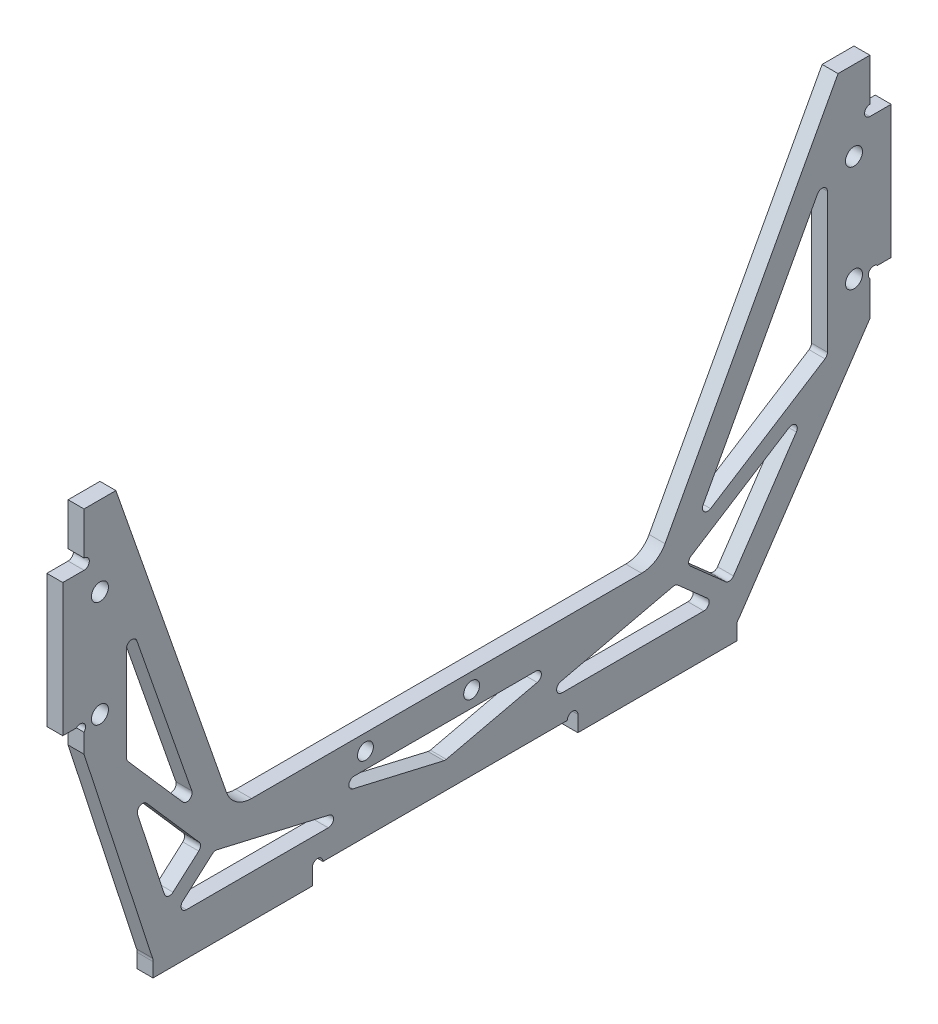
SolidWorks part; units mm, degrees
material "玻纤"
ref_plane "前视基准面" through (0, 0, 0) normal (0, 0, 1) x (1, 0, 0)
ref_plane "上视基准面" through (0, 0, 0) normal (0, 1, 0) x (1, 0, 0)
ref_plane "右视基准面" through (0, 0, 0) normal (1, 0, 0) x (0, 0, -1)
sketch "草图1" plane through (0, 0, 0) normal (1, 0, 0) x (0, 0, -1)
  line L0 (-74, -23) -> (74, -23)
  line L1 (-74, -40) -> (74, -40)
  line L2 (-74, -40) -> (-74, 40)
  line L3 (-74, 40) -> (74, 40)
  line L4 (74, -40) -> (74, 40)
  line L5 (-74, -40) -> (74, 40) construction
  line L6 (-74, 40) -> (74, -40) construction
  line L7 (-68, 40) -> (-46, -23)
  line L8 (34, -23) -> (68, 40)
  line L9 (-61, -40) -> (-74, -20.7267)
  line L10 (-61, -40) -> (-31, -40)
  line L11 (-61, -40) -> (-61, -43)
  line L12 (-61, -43) -> (-31, -43)
  line L13 (-31, -40) -> (-31, -43)
  line L14 (19, -40) -> (49, -40)
  line L15 (19, -40) -> (19, -43)
  line L16 (19, -43) -> (49, -43)
  line L17 (49, -40) -> (49, -43)
  line L18 (49, -40) -> (74, -2.936)
  point P0 (0, 0)
  dimension "D1" = 148
  dimension "D2" = 80
  dimension "D3" = 6
  dimension "D4" = 28
  dimension "D5" = 17
  dimension "D6" = 40
  dimension "D7" = 6
  dimension "D8" = 30
  dimension "D9" = 13
  dimension "D10" = 25
  dimension "D11" = 30
  dimension "D12" = 3
  dimension "D13" = 3
  dimension "D14" = 56
  dimension "D15" = 56
extrude "凸台-拉伸1" add sketch "草图1" along normal blind 3 contours L1 L4 L0 L2 | L7 L3 L2 L0 | L8 L0 L4 L3 | L13 L1 L11 L12 | L17 L1 L15 L16
sketch "草图2" plane through (3, 0, 0) normal (1, 0, 0) x (0, 0, -1)
  line L0 (-74, -20.7267) -> (-74, 40) construction
  line L1 (-74, 30) -> (-78, 30)
  line L2 (-74, 30) -> (-74, 5)
  line L3 (-74, 5) -> (-78, 5)
  line L4 (-78, 30) -> (-78, 5)
  line L5 (-31, -40) -> (19, -40) construction
  line L6 (74, -2.936) -> (74, 40) construction
  line L12 (74, 30) -> (78, 30)
  line L13 (74, 30) -> (74, 5)
  line L14 (74, 5) -> (78, 5)
  line L15 (78, 30) -> (78, 5)
  dimension "D1" = 4
  dimension "D2" = 25
  dimension "D3" = 45
  dimension "D4" = 4
extrude "凸台-拉伸2" add sketch "草图2" against normal blind 3
sketch "草图6" plane through (0, 0, 0) normal (-1, 0, 0) x (0, 0, 1)
  line L0 (-71, 40) -> (-71, 0) construction
  line L1 (-74, 40) -> (-68, 40) construction
  line L2 (-74, 40) -> (-74, 0) construction
  line L3 (-74, 0) -> (-68, 0) construction
  line L4 (-68, 40) -> (-68, 0) construction
  line L5 (0, 0) -> (0, -23) construction
  line L7 (46, -23) -> (-34, -23) construction
  line L8 (68, 40) -> (68, 0) construction
  line L9 (74, 0) -> (68, 0) construction
  line L10 (74, 40) -> (74, 0) construction
  line L11 (74, 40) -> (68, 40) construction
  line L12 (71, 40) -> (71, 0) construction
  circle A0 centre (-71, 25) radius 1.6
  circle A1 centre (-71, 5) radius 1.6
  circle A4 centre (71, 5) radius 1.6
  circle A5 centre (71, 25) radius 1.6
  dimension "D3" = 15
  dimension "D4" = 20
  dimension "D5" = 3.2
  dimension "D1" = 6
  dimension "D2" = 40
extrude "切除-拉伸4" cut sketch "草图6" against normal blind 4 contours A1 | A5 | A4 | A0
sketch "草图7" plane through (3, 0, 0) normal (1, 0, 0) x (0, 0, -1)
  line L0 (-66, 13.2098) -> (-66, -4.6242)
  line L3 (-53.6947, -16.1312) -> (-64.0559, 13.5395)
  line L5 (-68, 40) -> (-46, -23) construction
  line L6 (-78, 30) -> (-78, 5) construction
  line L7 (-65.7524, -5.2828) -> (-55.3913, -17.1195)
  line L9 (66, -4.4499) -> (66, 21.8078)
  line L18 (64.12, 22.2827) -> (42.5796, -17.6303)
  line L19 (34, -23) -> (68, 40) construction
  line L20 (78, 30) -> (78, 5) construction
  line L22 (-74, 0) -> (-61, -40)
  line L23 (-74, -20.7267) -> (-74, 5) construction
  line L24 (-61, -40) -> (-74, -20.7267)
  line L25 (-74, -20.7267) -> (-74, 0)
  line L26 (43.995, -18.9498) -> (65.5354, -5.2945)
  line L27 (-46, -23) -> (34, -23) construction
  line L28 (-62.2134, -13.8807) -> (-52.3073, -25.1974)
  line L29 (-52.3976, -26.6054) -> (-57.2363, -30.8807)
  line L30 (-58.8494, -30.4404) -> (-63.9168, -14.8484)
  line L31 (-55.3877, -33.2506) -> (-49.8314, -28.3412)
  line L32 (-48.9432, -28.1165) -> (-27.7828, -33.0259)
  line L33 (-28.0088, -35) -> (-54.7255, -35)
  line L34 (-23.1262, -29) -> (11.1262, -29)
  line L35 (11.3522, -30.9741) -> (-5.774, -34.9476)
  line L36 (-6.226, -34.9476) -> (-23.3522, -30.9741)
  line L37 (15.7828, -33.0259) -> (36.9432, -28.1165)
  line L38 (37.8314, -28.3412) -> (43.3877, -33.2506)
  line L39 (42.7255, -35) -> (16.0088, -35)
  line L40 (40.3205, -24.8313) -> (58.7839, -13.1266)
  line L41 (60.1484, -14.5304) -> (48.3069, -32.0861)
  line L42 (46.8157, -32.2763) -> (40.1938, -26.4253)
  line L43 (49, -40) -> (74, -2.936) construction
  line L44 (-6, -35) -> (-6, -40) construction
  line L45 (-31, -40) -> (19, -40) construction
  arc A0 (66, 21.8078) -> (64.12, 22.2827) centre (65, 21.8078) ccw
  arc A7 (-66, 13.2098) -> (-64.0559, 13.5395) centre (-65, 13.2098) cw
  circle A8 centre (-71, 5) radius 1.6 construction
  arc A9 (-66, -4.6242) -> (-65.7524, -5.2828) centre (-65, -4.6242) ccw
  arc A10 (-62.2134, -13.8807) -> (-63.9168, -14.8484) centre (-62.9658, -14.5393) ccw
  arc A11 (-53.6947, -16.1312) -> (-55.3913, -17.1195) centre (-54.6388, -16.4609) cw
  arc A12 (66, -4.4499) -> (65.5354, -5.2945) centre (65, -4.4499) cw
  arc A13 (42.5796, -17.6303) -> (43.995, -18.9498) centre (43.4596, -18.1052) ccw
  arc A14 (58.7839, -13.1266) -> (60.1484, -14.5304) centre (59.3194, -13.9712) cw
  arc A15 (48.3069, -32.0861) -> (46.8157, -32.2763) centre (47.4779, -31.5269) cw
  arc A16 (40.3205, -24.8313) -> (40.1938, -26.4253) centre (40.8559, -25.6759) ccw
  arc A17 (43.3877, -33.2506) -> (42.7255, -35) centre (42.7255, -34) cw
  arc A18 (36.9432, -28.1165) -> (37.8314, -28.3412) centre (37.1692, -29.0906) cw
  arc A19 (15.7828, -33.0259) -> (16.0088, -35) centre (16.0088, -34) ccw
  arc A20 (11.1262, -29) -> (11.3522, -30.9741) centre (11.1262, -30) cw
  arc A21 (-5.774, -34.9476) -> (-6.226, -34.9476) centre (-6, -33.9734) cw
  arc A22 (-49.8314, -28.3412) -> (-48.9432, -28.1165) centre (-49.1692, -29.0906) cw
  arc A23 (-23.1262, -29) -> (-23.3522, -30.9741) centre (-23.1262, -30) ccw
  arc A24 (-27.7828, -33.0259) -> (-28.0088, -35) centre (-28.0088, -34) cw
  arc A25 (-54.7255, -35) -> (-55.3877, -33.2506) centre (-54.7255, -34) cw
  arc A26 (-57.2363, -30.8807) -> (-58.8494, -30.4404) centre (-57.8984, -30.1313) cw
  arc A27 (-52.3073, -25.1974) -> (-52.3976, -26.6054) centre (-53.0598, -25.856) cw
  point P53 (-6, -29)
  point P72 (-66, -5)
  point P77 (-51.9945, -21)
  point P80 (66, -5)
  point P83 (40.761, -21)
  point P94 (37.4452, -28)
  point P104 (-49.4452, -28)
  point P109 (-19.274, -35)
  point P112 (-57.3676, -35)
  dimension "D6" = 12
  dimension "D9" = 1
  dimension "D2" = 1
  dimension "D24" = 1
  dimension "D1" = 5
  dimension "D3" = 12
  dimension "D4" = 2
  dimension "D5" = 5
  dimension "D7" = 10
  dimension "D8" = 5
  dimension "D10" = 3
  dimension "D11" = 5
  dimension "D12" = 5
  dimension "D13" = 3
  dimension "D14" = 3
  dimension "D15" = 5
  dimension "D16" = 5
  dimension "D17" = 5
  dimension "D18" = 3
  dimension "D19" = 3
  dimension "D20" = 3
  dimension "D21" = 5
  dimension "D22" = 5
  dimension "D23" = 6
extrude "切除-拉伸5" cut sketch "草图7" against normal blind 10
sketch "草图10" plane through (0, 0, 0) normal (-1, 0, 0) x (0, 0, 1)
  line L0 (61, -40) -> (61, -43) construction
  line L1 (-74, 30) -> (-78, 30) construction
  line L2 (-74, 30) -> (-74, 40) construction
  line L3 (61, -40) -> (74, 0) construction
  line L4 (61.0967, -39.7024) -> (61, -40.3129)
  line L5 (61, -40) -> (61.0484, -40.0077) construction
  line L7 (-74, 30) -> (-74, 32)
  line L8 (74, 30) -> (74, 32)
  line L9 (74, 30) -> (74, 40) construction
  line L10 (-74, -2.936) -> (-74, 5) construction
  line L11 (-74, 5) -> (-78, 5) construction
  line L12 (-74, 3.5858) -> (-75.4142, 5)
  line L13 (74, 5) -> (78, 5) construction
  line L14 (74, 0) -> (74, 5) construction
  line L15 (74, 3.5858) -> (75.4142, 5)
  line L16 (31, -40) -> (-19, -40) construction
  line L17 (-17, -40) -> (-19, -40)
  line L18 (31, -40) -> (31, -43) construction
  line L19 (29, -40) -> (31, -40)
  line L21 (-49, -40) -> (-74, -2.936) construction
  line L22 (-49, -40) -> (-49, -43) construction
  line L23 (-49.327, -39.5152) -> (-49, -40.5847)
  line L24 (-49.1635, -40.05) -> (-49, -40) construction
  arc A8 (-74, 32) -> (-74, 30) centre (-74, 31) cw
  arc A9 (74, 30) -> (74, 32) centre (74, 31) cw
  arc A10 (-74, 3.5858) -> (-75.4142, 5) centre (-74.7071, 4.2929) ccw
  arc A11 (75.4142, 5) -> (74, 3.5858) centre (74.7071, 4.2929) ccw
  arc A12 (-19, -40) -> (-17, -40) centre (-18, -40) cw
  arc A13 (31, -40) -> (29, -40) centre (30, -40) ccw
  arc A14 (-49.327, -39.5152) -> (-49, -40.5847) centre (-49.9563, -40.2924) cw
  arc A15 (61, -40.3129) -> (61.0967, -39.7024) centre (61.9877, -40.1565) cw
  dimension "D1" = 1
  dimension "D2" = 45
  dimension "D3" = 45
  dimension "D4" = 1
  dimension "D5" = 1
  dimension "D6" = 1
extrude "切除-拉伸7" cut sketch "草图10" against normal blind 10
fillet "圆角1" radius 5 2 edges at (1.5, -23, -34) (1.5, -23, 46)
sketch "草图11" plane through (3, 0, 0) normal (1, 0, 0) x (0, 0, -1)
  line L0 (-6, -40) -> (-6, -14.1155) construction
  line L2 (-42.4499, -23) -> (31.0167, -23) construction
  line L3 (-1, -26) -> (-21, -26) construction
  line L5 (-29, -40) -> (17, -40) construction
  circle A0 centre (-1, -26) radius 1.5
  circle A1 centre (-21, -26) radius 1.5
  dimension "D1" = 20
  dimension "D2" = 3
  dimension "D3" = 3
  dimension "D4" = 5
extrude "切除-拉伸8" cut sketch "草图11" against normal through all
